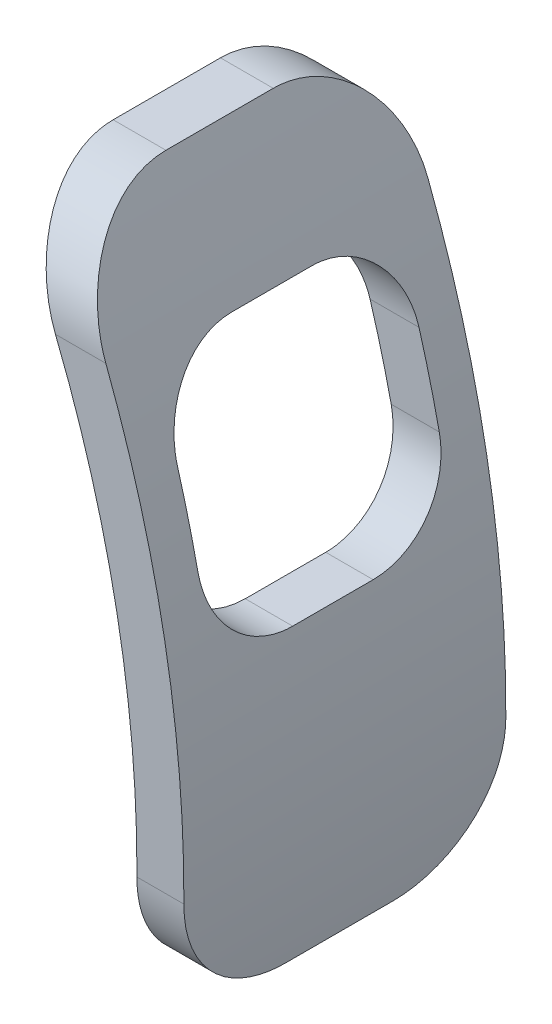
SolidWorks part; units mm, degrees
ref_plane "Front Plane" through (0, 0, 0) normal (0, 0, 1) x (1, 0, 0)
ref_plane "Top Plane" through (0, 0, 0) normal (0, 1, 0) x (1, 0, 0)
ref_plane "Right Plane" through (0, 0, 0) normal (1, 0, 0) x (0, 0, -1)
sketch "Sketch1" plane through (0, 0, 0) normal (0, 0, 1) x (1, 0, 0)
  line L0 (-2063.2072, -609.6) -> (2063.2072, -609.6) construction
  line L1 (-2087.4164, -520.7) -> (2087.4164, -520.7) construction
  line L2 (2003.0586, 1003.3) -> (2003.0586, -215.9) construction
  line L3 (2003.0586, -215.9) -> (2229.8524, -215.9) construction
  line L4 (1903.1093, 1003.3) -> (2003.0586, 1003.3)
  line L5 (2140.5194, -215.9) -> (2229.8524, -215.9)
  line L6 (1903.1093, 1003.3) -> (1903.1093, -215.9) construction
  circle A0 centre (0, 0) radius 2240.28 construction
  circle A1 centre (0, 0) radius 2151.38 construction
  arc A2 (2229.8524, -215.9) -> (2003.0586, 1003.3) centre (0, 0) ccw
  arc A3 (2140.5194, -215.9) -> (1903.1093, 1003.3) centre (0, 0) ccw
  point P6 (0, -2151.38)
  dimension "D1" = 4480.56
  dimension "D2" = 88.9
  dimension "D5" = 1219.2
  dimension "D7" = 1219.2
  dimension "D3" = 1541.78
  dimension "D4" = 88.9
  dimension "D6" = 304.8
extrude "Boss-Extrude2" add sketch "Sketch1" along normal blind 609.6
fillet "Fillet1" radius 203.2 4 edges at (2185.1859, -215.9, 0) (2185.1859, -215.9, 609.6) (1953.0839, 1003.3, 0) (1953.0839, 1003.3, 609.6)
sketch "Sketch2" plane through (0, 0, 0) normal (1, 0, 0) x (0, 0, -1)
  line L0 (-406.4, 1003.3) -> (-203.2, 1003.3) construction
  line L1 (-381, 317.5) -> (-228.6, 317.5)
  line L2 (-533.4, 469.9) -> (-533.4, 622.3)
  line L3 (-381, 774.7) -> (-228.6, 774.7)
  line L4 (-76.2, 469.9) -> (-76.2, 622.3)
  line L5 (-533.4, 317.5) -> (-76.2, 774.7) construction
  line L6 (-533.4, 774.7) -> (-76.2, 317.5) construction
  arc A0 (-381, 317.5) -> (-533.4, 469.9) centre (-381, 469.9) cw
  arc A1 (-76.2, 469.9) -> (-228.6, 317.5) centre (-228.6, 469.9) cw
  arc A2 (-76.2, 622.3) -> (-228.6, 774.7) centre (-228.6, 622.3) ccw
  arc A3 (-381, 774.7) -> (-533.4, 622.3) centre (-381, 622.3) ccw
  point P0 (-304.8, 546.1)
  point P9 (-304.8, 1003.3)
  dimension "D2" = 152.4
  dimension "D1" = 457.2
  dimension "D3" = 457.2
  dimension "D4" = 457.2
extrude "Cut-Extrude1" cut sketch "Sketch2" against normal through all both and the other way through all
